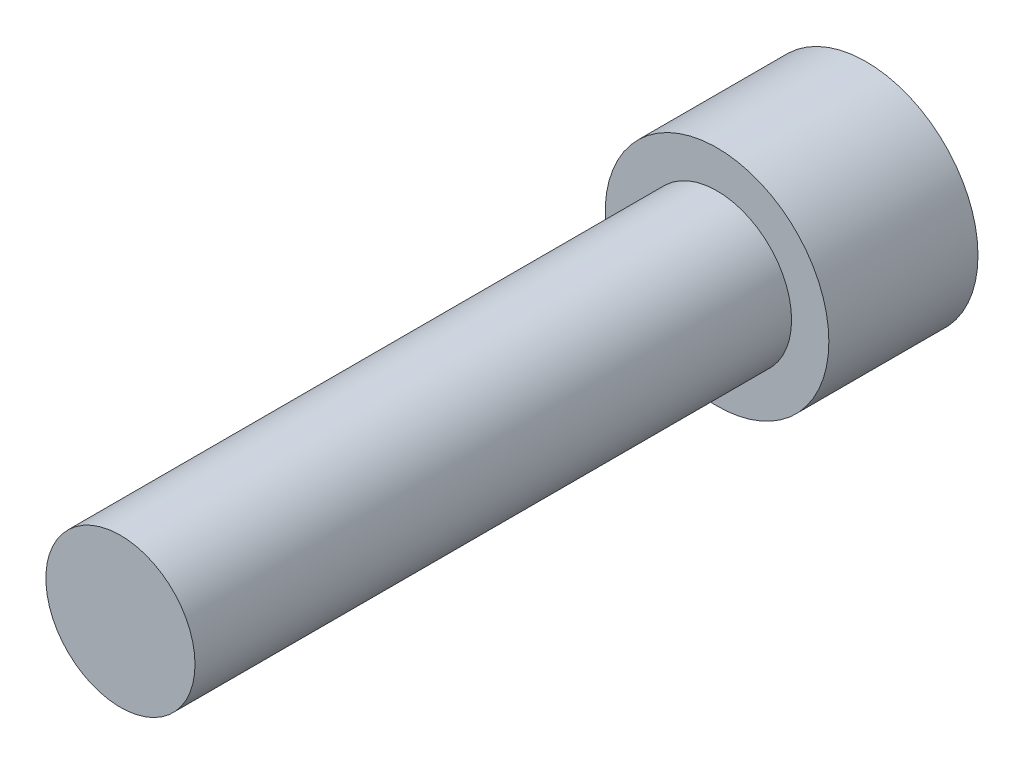
SolidWorks part; units mm, degrees
ref_plane "Front Plane" through (0, 0, 0) normal (0, 0, 1) x (1, 0, 0)
ref_plane "Top Plane" through (0, 0, 0) normal (0, 1, 0) x (1, 0, 0)
ref_plane "Right Plane" through (0, 0, 0) normal (1, 0, 0) x (0, 0, -1)
sketch "Sketch2" plane through (0, 0, 0) normal (0, 0, 1) x (1, 0, 0)
  circle A0 centre (0, 0) radius 7.5
  dimension "D1" = 15
extrude "Boss-Extrude3" add sketch "Sketch2" along normal blind 10
sketch "Sketch3" plane through (0, 0, 0) normal (0, 0, -1) x (-1, 0, 0)
  line L1 (2.8868, 5) -> (-2.8868, 5)
  line L2 (-2.8868, 5) -> (-5.7735, 0)
  line L3 (-5.7735, 0) -> (-2.8868, -5)
  line L4 (-2.8868, -5) -> (2.8868, -5)
  line L5 (2.8868, -5) -> (5.7735, 0)
  line L6 (5.7735, 0) -> (2.8868, 5)
  circle A0 centre (0, 0) radius 5 construction
  dimension "D1" = 10
sketch "Sketch4" plane through (0, 0, 10) normal (0, 0, 1) x (1, 0, 0)
  circle A0 centre (0, 0) radius 5
  dimension "D1" = 10
extrude "Boss-Extrude4" add sketch "Sketch4" along normal blind 40
extrude "Cut-Extrude1" cut sketch "Sketch3" against normal blind 7
